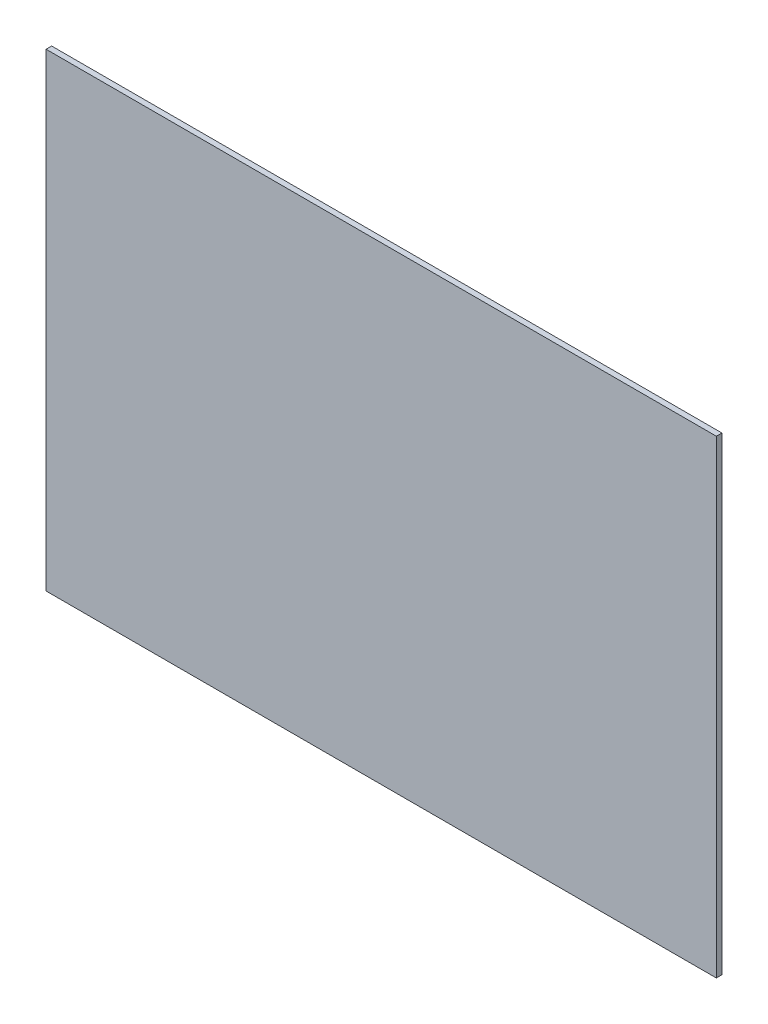
SolidWorks part; units mm, degrees
ref_plane "Front Plane" through (0, 0, 0) normal (0, 0, 1) x (1, 0, 0)
ref_plane "Top Plane" through (0, 0, 0) normal (0, 1, 0) x (1, 0, 0)
ref_plane "Right Plane" through (0, 0, 0) normal (1, 0, 0) x (0, 0, -1)
sketch "Sketch1" plane through (0, 0, 0) normal (0, 0, 1) x (1, 0, 0)
  line L1 (0, 0) -> (190.5, 0)
  line L2 (0, 0) -> (0, 133.35)
  line L3 (0, 133.35) -> (190.5, 133.35)
  line L4 (190.5, 0) -> (190.5, 133.35)
  dimension "D1" = 133.35
  dimension "D2" = 190.5
extrude "Boss-Extrude1" add sketch "Sketch1" along normal blind 1.5875
